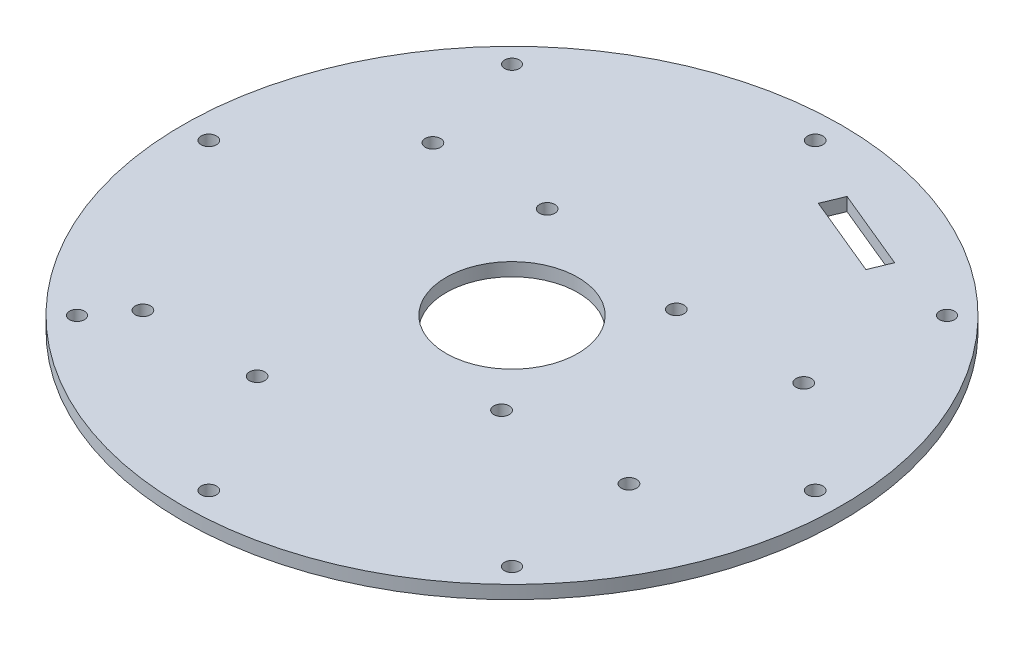
SolidWorks part; units mm, degrees
ref_plane "Front Plane" through (0, 0, 0) normal (0, 0, 1) x (1, 0, 0)
ref_plane "Top Plane" through (0, 0, 0) normal (0, 1, 0) x (1, 0, 0)
ref_plane "Right Plane" through (0, 0, 0) normal (1, 0, 0) x (0, 0, -1)
sketch "Sketch1" plane through (0, 0, 0) normal (0, 1, 0) x (1, 0, 0)
  line L0 (-49.4975, -49.4975) -> (49.4975, 49.4975) construction
  line L1 (49.4975, -49.4975) -> (-49.4975, 49.4975) construction
  line L2 (0, 0) -> (130.1462, 0) construction
  circle A1 centre (0, 0) radius 75
  circle A6 centre (0, 0) radius 70 construction
  circle A7 centre (49.4975, 49.4975) radius 1.7
  circle A8 centre (-49.4975, 49.4975) radius 1.7
  circle A9 centre (-49.4975, -49.4975) radius 1.7
  circle A10 centre (49.4975, -49.4975) radius 1.7
  circle A11 centre (0, 0) radius 15
  point P15 (0, 0)
  point P19 (0, 0)
  dimension "D3" = 150
  dimension "D4" = 140
  dimension "D6" = 3.4
  dimension "D7" = 30
  dimension "D5" = 45
extrude "Boss-Extrude1" add sketch "Sketch1" along normal blind 3
sketch "Sketch2" plane through (0, 0, 0) normal (0, 1, 0) x (1, 0, 0)
  circle A0 centre (0, 0) radius 69 construction
  circle A1 centre (0, 69) radius 1.75
  circle A2 centre (69, 0) radius 1.75
  circle A3 centre (0, -69) radius 1.75
  circle A4 centre (-69, 0) radius 1.75
  dimension "D1" = 138
  dimension "D2" = 3.5
extrude "Cut-Extrude2" cut sketch "Sketch2" along normal through all
sketch "Sketch3" plane through (0, 0, 0) normal (0, 1, 0) x (1, 0, 0)
  line L0 (-30, 0) -> (32, 0) construction
  line L9 (-43, -41) -> (-17, -41) construction
  line L10 (-43, -41) -> (-43, 25) construction
  line L11 (-43, 25) -> (-17, 25) construction
  line L12 (-17, -41) -> (-17, 25) construction
  line L13 (-43, -41) -> (-17, 25) construction
  line L14 (-43, 25) -> (-17, -41) construction
  line L15 (46.4944, -19.8841) -> (17.5056, -19.8841) construction
  line L16 (46.4944, -19.8841) -> (46.4944, 19.8841) construction
  line L17 (46.4944, 19.8841) -> (17.5056, 19.8841) construction
  line L18 (17.5056, -19.8841) -> (17.5056, 19.8841) construction
  line L19 (46.4944, -19.8841) -> (17.5056, 19.8841) construction
  line L20 (46.4944, 19.8841) -> (17.5056, -19.8841) construction
  line L21 (31.2431, 49.2962) -> (12.7655, 56.9499)
  line L22 (-45, 27) -> (-15, 27) construction
  line L23 (-45, 27) -> (-45, -43) construction
  line L24 (-45, -43) -> (-15, -43) construction
  line L25 (-15, 27) -> (-15, -43) construction
  line L30 (31.2431, 49.2962) -> (33.1565, 53.9156)
  line L31 (12.7655, 56.9499) -> (14.6789, 61.5693)
  line L32 (33.1565, 53.9156) -> (14.6789, 61.5693)
  line L33 (31.2431, 49.2962) -> (14.6789, 61.5693) construction
  line L34 (12.7655, 56.9499) -> (33.1565, 53.9156) construction
  line L35 (0, 0) -> (22.961, 55.4328) construction
  circle A0 centre (-43, 25) radius 1.75
  circle A1 centre (-17, 25) radius 1.75
  circle A2 centre (-17, -41) radius 1.75
  circle A3 centre (-43, -41) radius 1.75
  circle A4 centre (17.5056, 19.8841) radius 1.75
  circle A5 centre (46.4944, -19.8841) radius 1.75
  circle A6 centre (46.4944, 19.8841) radius 1.75
  circle A7 centre (17.5056, -19.8841) radius 1.75
  circle A8 centre (0, 0) radius 63.5 construction
  point P0 (-30, -8)
  point P5 (32, 0)
  point P28 (22.961, 55.4328)
  dimension "D5" = 3.5
  dimension "D9" = 127
  dimension "D1" = 30
  dimension "D2" = 32
  dimension "D3" = 26
  dimension "D4" = 66
  dimension "D6" = 49.2125
  dimension "D7" = 53.91
  dimension "D8" = 8
  dimension "D10" = 2
  dimension "D11" = 2
  dimension "D12" = 2
  dimension "D13" = 2
  dimension "D14" = 5
  dimension "D15" = 20
  dimension "D16" = 67.5
  dimension "D17" = 60
extrude "Cut-Extrude3" cut sketch "Sketch3" along normal through all
